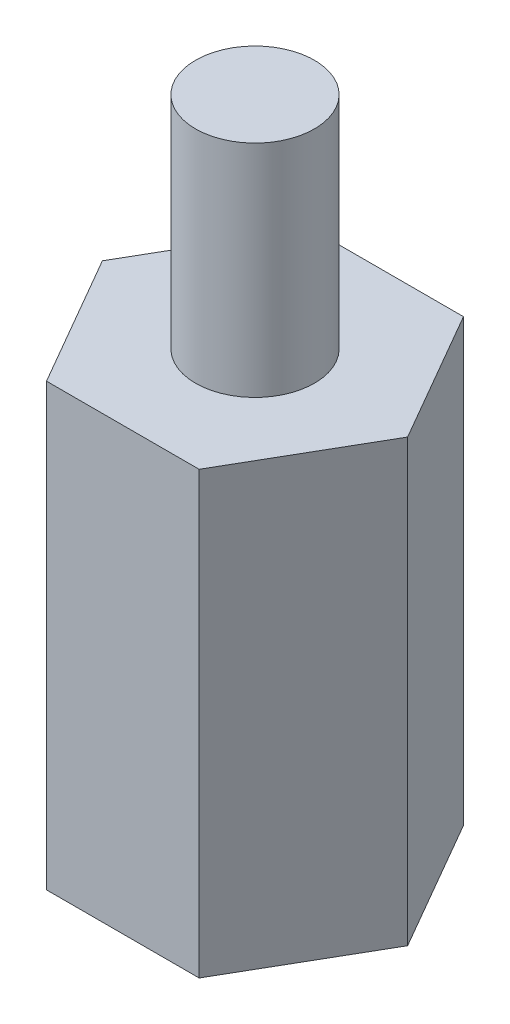
SolidWorks part; units mm, degrees
ref_plane "정면도" through (0, 0, 0) normal (0, 0, 1) x (1, 0, 0)
ref_plane "평면도" through (0, 0, 0) normal (0, 1, 0) x (1, 0, 0)
ref_plane "우측면도" through (0, 0, 0) normal (1, 0, 0) x (0, 0, -1)
sketch "스케치1" plane through (0, 0, 0) normal (0, 1, 0) x (1, 0, 0)
  line L1 (3.4641, 0) -> (1.7321, 3)
  line L2 (1.7321, 3) -> (-1.7321, 3)
  line L3 (-1.7321, 3) -> (-3.4641, 0)
  line L4 (-3.4641, 0) -> (-1.7321, -3)
  line L5 (-1.7321, -3) -> (1.7321, -3)
  line L6 (1.7321, -3) -> (3.4641, 0)
  circle A0 centre (0, 0) radius 3 construction
  dimension "D1" = 6
extrude "보스-돌출1" add sketch "스케치1" along normal blind 10
sketch "스케치2" plane through (0, 10, 0) normal (0, 1, 0) x (1, 0, 0)
  circle A0 centre (0, 0) radius 1.35
  dimension "D1" = 2.7
extrude "보스-돌출2" add sketch "스케치2" along normal blind 5
sketch "스케치3" plane through (0, 0, 0) normal (0, -1, 0) x (1, 0, 0)
  circle A0 centre (0, 0) radius 1.35
  dimension "D1" = 2.7
extrude "컷-돌출1" cut sketch "스케치3" against normal blind 6
